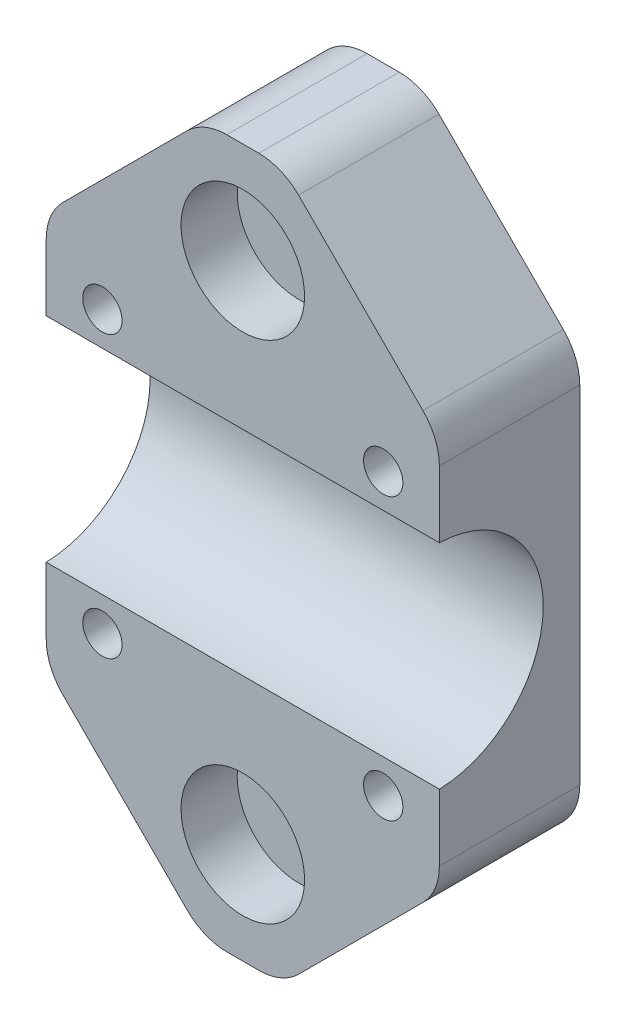
SolidWorks part; units mm, degrees
ref_plane "XY" through (0, 0, 0) normal (0, 0, 1) x (1, 0, 0)
ref_plane "XZ" through (0, 0, 0) normal (0, 1, 0) x (1, 0, 0)
ref_plane "YZ" through (0, 0, 0) normal (1, 0, 0) x (0, 0, -1)
sketch "Sketch1" plane through (0, 0, 0) normal (0, 0, 1) x (1, 0, 0)
  line L0 (-3.5, 31.5) -> (-17.5, 17.5)
  line L1 (17.5, 31.5) -> (3.5, 31.5) construction
  line L2 (17.5, 31.5) -> (17.5, 17.5) construction
  line L3 (17.5, -31.5) -> (3.5, -31.5) construction
  line L4 (-17.5, 31.5) -> (-17.5, 17.5) construction
  line L5 (17.5, 31.5) -> (-17.5, -31.5) construction
  line L6 (17.5, -31.5) -> (-17.5, 31.5) construction
  line L7 (0, 0) -> (0, 36.1303) construction
  line L8 (0, 0) -> (-42.5592, 0) construction
  line L9 (3.5, 31.5) -> (17.5, 17.5)
  line L10 (3.5, -31.5) -> (17.5, -17.5)
  line L11 (-3.5, -31.5) -> (-17.5, -17.5)
  line L12 (-17.5, 17.5) -> (-17.5, -17.5)
  line L13 (-17.5, -17.5) -> (-17.5, -31.5) construction
  line L14 (17.5, -17.5) -> (17.5, -31.5) construction
  line L15 (17.5, 17.5) -> (17.5, -17.5)
  line L16 (-3.5, 31.5) -> (-17.5, 31.5) construction
  line L17 (3.5, 31.5) -> (-3.5, 31.5)
  line L18 (-3.5, -31.5) -> (-17.5, -31.5) construction
  line L19 (3.5, -31.5) -> (-3.5, -31.5)
  point P0 (0, 0)
  dimension "D1" = 35
  dimension "D2" = 63
  dimension "D3" = 14
  dimension "D4" = 14
extrude "Boss-Extrude1" add sketch "Sketch1" along normal blind 12.5
sketch "Sketch2" plane through (17.5, 0, 0) normal (1, 0, 0) x (0, 0, -1)
  line L0 (-12.5, -17.5) -> (-12.5, 17.5) construction
  line L1 (-12.5, -9.4967) -> (-12.5, 9.4967)
  arc A0 (-12.5, -9.4967) -> (-12.5, 9.4967) centre (-12.75, 0) ccw
  dimension "D1" = 19
  dimension "D2" = 12.75
extrude "Cut-Extrude1" cut sketch "Sketch2" against normal up to next
sketch "Sketch3" plane through (0, 0, 0) normal (0, 0, -1) x (-1, 0, 0)
  line L0 (0, 0) -> (0, 20.4714) construction
  line L1 (0, 0) -> (-26.9924, 0) construction
  circle A0 centre (-12.5, 12.5) radius 3
  circle A1 centre (12.5, 12.5) radius 3
  circle A2 centre (12.5, -12.5) radius 3
  circle A3 centre (-12.5, -12.5) radius 3
  dimension "D1" = 6
  dimension "D2" = 12.5
  dimension "D3" = 12.5
extrude "Cut-Extrude2" cut sketch "Sketch3" against normal blind 3
sketch "Sketch4" plane through (0, 0, 12.5) normal (0, 0, 1) x (1, 0, 0)
  line L0 (-0.6363, 0) -> (39.3124, 0) construction
  circle A0 centre (0, 22.5) radius 5.5
  circle A1 centre (0, -22.5) radius 5.5
  dimension "D1" = 11
  dimension "D2" = 22.5
extrude "Cut-Extrude3" cut sketch "Sketch4" against normal blind 5
fillet "Fillet1" radius 5 8 edges at (-3.5, -31.5, 6.25) (3.5, -31.5, 6.25) (17.5, -17.5, 6.25) (17.5, 17.5, 6.25) (-17.5, -17.5, 6.25) (3.5, 31.5, 6.25) (-3.5, 31.5, 6.25) (-17.5, 17.5, 6.25)
sketch "Sketch5" plane through (0, 0, 12.5) normal (0, 0, 1) x (1, 0, 0)
  line L0 (0, 0) -> (0, 13.9425) construction
  line L1 (0, 0) -> (-26.6208, 0) construction
  circle A0 centre (-12.5, 12.5) radius 1.75
  circle A1 centre (12.5, 12.5) radius 1.75
  circle A2 centre (12.5, -12.5) radius 1.75
  circle A3 centre (-12.5, -12.5) radius 1.75
  dimension "D1" = 12.5
  dimension "D3" = 3.5
  dimension "D2" = 12.5
extrude "Cut-Extrude4" cut sketch "Sketch5" against normal blind 9.1
